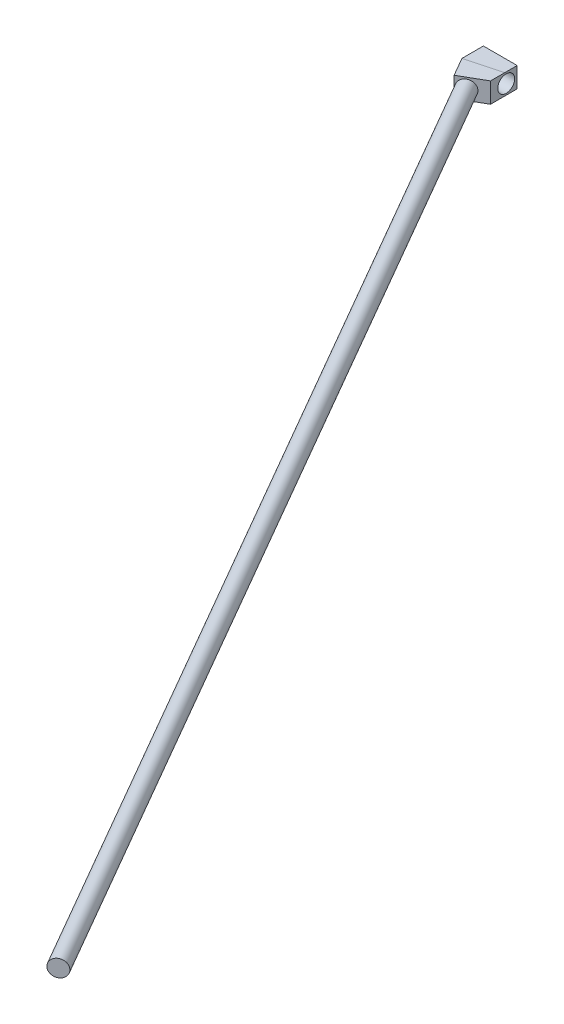
SolidWorks part; units mm, degrees
ref_plane "Front Plane" through (0, 0, 0) normal (0, 0, 1) x (1, 0, 0)
ref_plane "Top Plane" through (0, 0, 0) normal (0, 1, 0) x (1, 0, 0)
ref_plane "Right Plane" through (0, 0, 0) normal (1, 0, 0) x (0, 0, -1)
sketch "Sketch1" plane through (0, 0, 0) normal (0, 0, 1) x (1, 0, 0)
  line L1 (-5, 3) -> (5, 3)
  line L2 (-5, 3) -> (-5, -3)
  line L3 (-5, -3) -> (5, -3)
  line L4 (5, 3) -> (5, -3)
  line L5 (-5, 3) -> (5, -3) construction
  line L6 (-5, -3) -> (5, 3) construction
  point P0 (0, 0)
  dimension "D1" = 10
  dimension "D2" = 6
sketch "Sketch4" plane through (0, 0, 0) normal (0, 1, 0) x (1, 0, 0)
  line L0 (0, 0) -> (0, -5)
  line L1 (0, -5) -> (2.5, -9.3301)
  dimension "D1" = 5
  dimension "D2" = 5
  dimension "D3" = 150
sweep "Sweep2" add profiles "Sketch1" path "Sketch4"
sketch "Sketch5" plane through (-5, 0, 0) normal (-1, 0, 0) x (0, 0, 1)
  circle A0 centre (3.2458, 0) radius 2.5
  dimension "D1" = 5
extrude "Cut-Extrude1" cut sketch "Sketch5" against normal through all
ref_plane "Plane1" through (5, 0, 0) normal (1, 0, 0) x (0, 0, -1)
other "SurfaceCut1"
sketch "Sketch6" plane through (4.6651, 0, 8.0801) normal (0.5, 0, 0.866) x (0.866, 0, -0.5)
  circle A0 centre (-4.8373, 0) radius 2.5
extrude "Boss-Extrude1" add sketch "Sketch6" along normal blind 330
